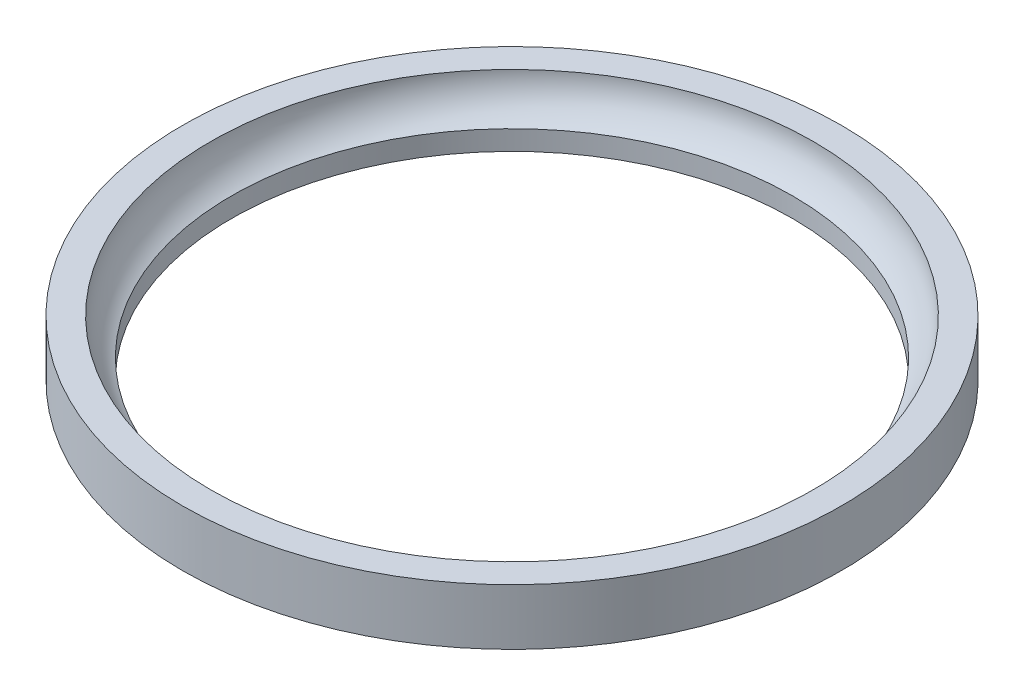
SolidWorks part; units mm, degrees
material "Plain Carbon Steel"
ref_plane "Front Plane" through (0, 0, 0) normal (0, 0, 1) x (1, 0, 0)
ref_plane "Top Plane" through (0, 0, 0) normal (0, 1, 0) x (1, 0, 0)
ref_plane "Right Plane" through (0, 0, 0) normal (1, 0, 0) x (0, 0, -1)
sketch "Sketch2" plane through (0, 0, 0) normal (0, 0, 1) x (1, 0, 0)
  line L0 (0, 0) -> (10, 0) construction
  line L1 (10, 0) -> (10, -0.701)
  line L2 (10, -0.701) -> (11.75, -0.701)
  line L3 (11.75, -0.701) -> (11.75, 1.299)
  line L4 (11.75, 1.299) -> (10.75, 1.299)
  line L5 (0, 0) -> (0, 1.299) construction
  arc A0 (10.75, 1.299) -> (10, 0) centre (9.25, 1.299) cw
  dimension "D4" = 1.5
  dimension "D1" = 1
  dimension "D2" = 2
  dimension "D3" = 1.75
  dimension "D5" = 10
revolve "Revolve1" add sketch "Sketch2" angle 360 about L5
